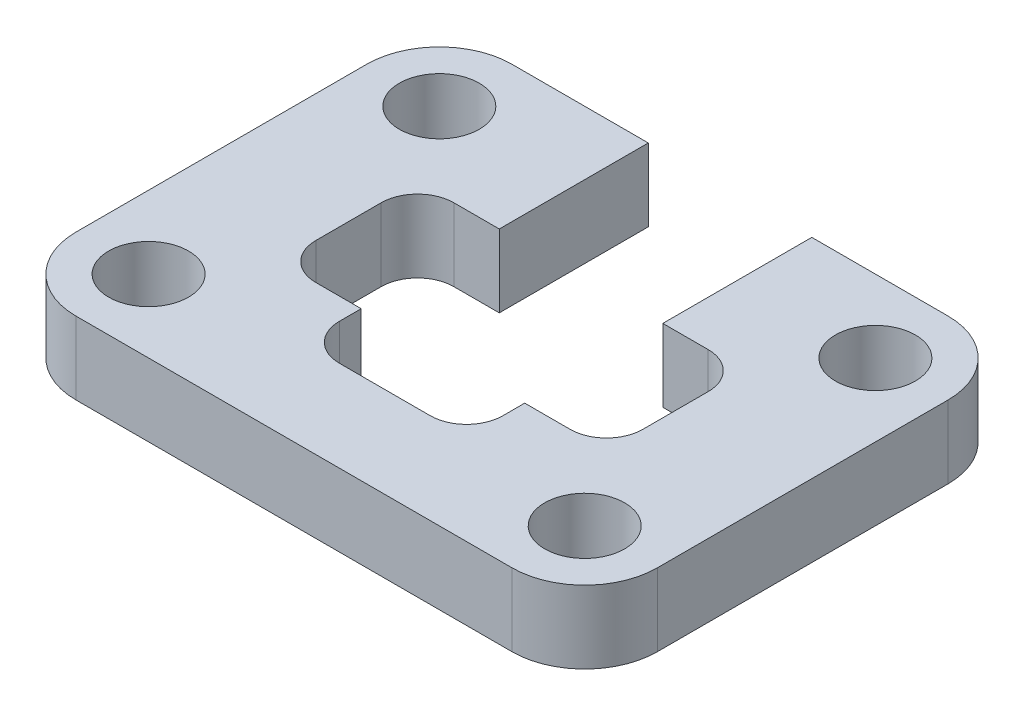
SolidWorks part; units mm, degrees
material "Thornel Mat VMA"
ref_plane "前视基准面" through (0, 0, 0) normal (0, 0, 1) x (1, 0, 0)
ref_plane "上视基准面" through (0, 0, 0) normal (0, 1, 0) x (1, 0, 0)
ref_plane "右视基准面" through (0, 0, 0) normal (1, 0, 0) x (0, 0, -1)
sketch "草图1" plane through (0, 0, 0) normal (0, 1, 0) x (1, 0, 0)
  line L1 (-8, -6) -> (8, -6)
  line L2 (-8, -6) -> (-8, 6)
  line L3 (-8, 6) -> (8, 6)
  line L4 (8, -6) -> (8, 6)
  line L5 (0, 6) -> (0, -6) construction
  line L6 (-8, 0) -> (8, 0) construction
  line L7 (-2.25, -3.5) -> (2.25, -3.5)
  line L8 (-2.25, -3.5) -> (-2.25, 6)
  line L9 (-2.25, 6) -> (2.25, 6)
  line L10 (2.25, -3.5) -> (2.25, 6)
  line L11 (0, 6) -> (0, -3.5) construction
  line L12 (-2.25, 1.25) -> (2.25, 1.25) construction
  circle A0 centre (-6, 4) radius 1.1
  circle A1 centre (-6, -4) radius 1.1
  circle A2 centre (6, -4) radius 1.1
  circle A3 centre (6, 4) radius 1.1
  point P0 (0, 0)
  point P12 (0, 1.25)
  dimension "D5" = 2.2
  dimension "D1" = 16
  dimension "D2" = 12
  dimension "D3" = 12
  dimension "D4" = 8
  dimension "D6" = 4.5
  dimension "D7" = 2.5
extrude "凸台-拉伸1" add sketch "草图1" along normal blind 2 contours L10 L7 L8 L3 L2 L1 L4 A1 A0 A2 A3
sketch "草图2" plane through (0, 2, 0) normal (0, 1, 0) x (1, 0, 0)
  line L1 (-4.5, 1.9) -> (4.5, 1.9)
  line L2 (-4.5, 1.9) -> (-4.5, -1.9)
  line L3 (-4.5, -1.9) -> (4.5, -1.9)
  line L4 (4.5, 1.9) -> (4.5, -1.9)
  line L5 (0, -1.9) -> (0, 1.9) construction
  line L6 (-4.5, 0) -> (4.5, 0) construction
  point P0 (0, 0)
  dimension "D1" = 3.8
  dimension "D2" = 9
extrude "切除-拉伸1" cut sketch "草图2" against normal through all
fillet "圆角1" radius 2 4 edges at (-8, 1, 6) (8, 1, 6) (8, 1, -6) (-8, 1, -6)
fillet "圆角2" radius 1 6 edges at (4.5, 1, 1.9) (4.5, 1, -1.9) (-4.5, 1, -1.9) (2.25, 1, 3.5) (-2.25, 1, 3.5) (-4.5, 1, 1.9)
